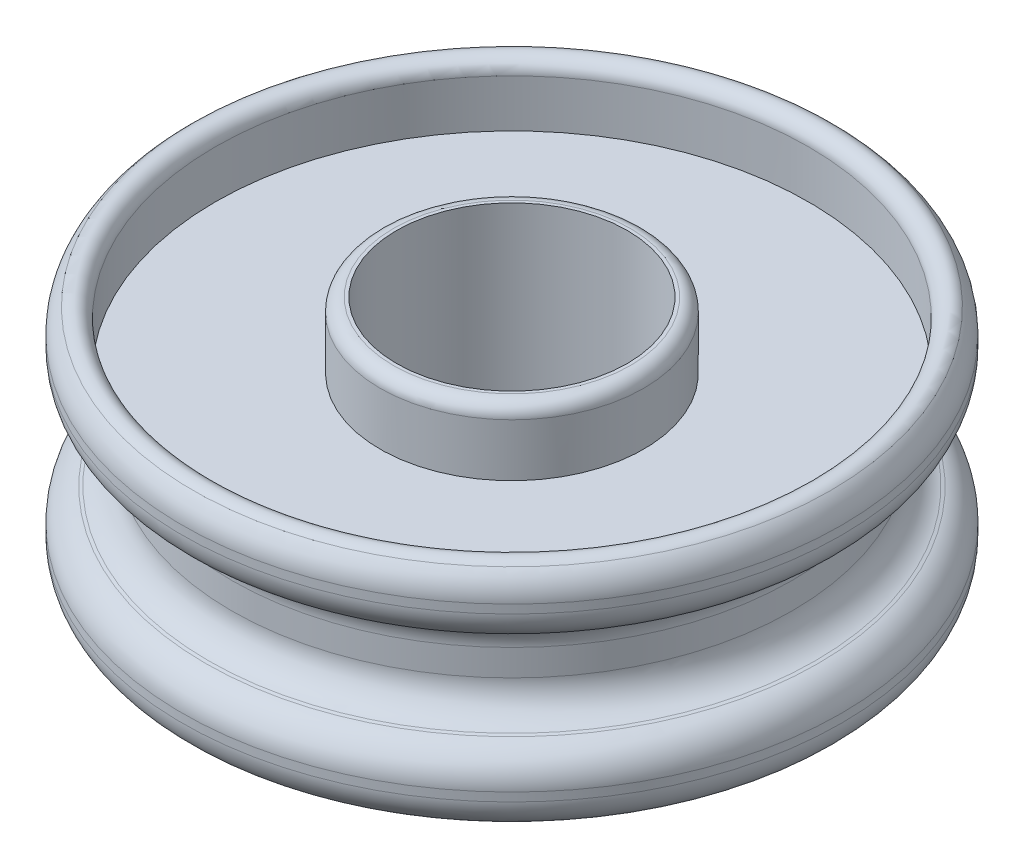
SolidWorks part; units mm, degrees
ref_plane "Front Plane" through (0, 0, 0) normal (0, 0, 1) x (1, 0, 0)
ref_plane "Top Plane" through (0, 0, 0) normal (0, 1, 0) x (1, 0, 0)
ref_plane "Right Plane" through (0, 0, 0) normal (1, 0, 0) x (0, 0, -1)
sketch "Sketch1" plane through (0, 0, 0) normal (0, 0, 1) x (1, 0, 0)
  line L0 (-1819.5005, 0) -> (89155.5226, 0) construction
  line L1 (0, -1819.5005) -> (0, 89155.5226) construction
  line L2 (17.5, 0) -> (45, 0)
  line L3 (50, -5) -> (50, -6.3066)
  line L4 (46.4698, -11.0857) -> (46.0302, -11.2209)
  line L5 (42.5, -16) -> (42.5, -20)
  line L6 (-957.5, -18) -> (49042.5, -18) construction
  line L7 (46.4698, -24.9143) -> (46.0302, -24.7791)
  line L8 (17.5, -36) -> (45, -36)
  line L9 (17.5, 0) -> (17.5, -36)
  line L10 (50, -29.6934) -> (50, -31)
  line L11 (50, -29.6934) -> (50, -31)
  arc A0 (42.5, -16) -> (46.0302, -11.2209) centre (47.5, -16) cw
  arc A1 (46.4698, -11.0857) -> (50, -6.3066) centre (45, -6.3066) ccw
  arc A2 (50, -5) -> (45, 0) centre (45, -5) ccw
  arc A3 (42.5, -20) -> (46.0302, -24.7791) centre (47.5, -20) ccw
  arc A4 (46.4698, -24.9143) -> (50, -29.6934) centre (45, -29.6934) cw
  arc A5 (50, -31) -> (45, -36) centre (45, -31) cw
  point P14 (50, -10)
  point P17 (50, 0)
  point P21 (42.5, -18)
  dimension "D5" = 5
  dimension "D1" = 50
  dimension "D2" = 17.5
  dimension "D3" = 10
  dimension "D4" = 42.5
  dimension "D6" = 2
  dimension "D7" = 6
revolve "Revolve1" add sketch "Sketch1" angle 360 about L1
sketch "Sketch2" plane through (0, 0, 0) normal (0, 1, 0) x (1, 0, 0)
  circle A0 centre (0, 0) radius 73.789
  circle A1 centre (0, 0) radius 20
  circle A2 centre (0, 0) radius 45 construction
  circle A3 centre (0, 0) radius 45
  dimension "D1" = 40
extrude "Cut-Extrude1" cut sketch "Sketch2" against normal blind 10 contours A3 | A1
fillet "Fillet2" radius 2 1 edges at (-45, 0, 0)
fillet "Fillet3" radius 2 1 edges at (-20, 0, 0)
sketch "Sketch3" plane through (0, -36, 0) normal (0, -1, 0) x (1, 0, 0)
  circle A0 centre (0, 0) radius 20
  circle A1 centre (0, 0) radius 45
  circle A2 centre (0, 0) radius 45
  dimension "D2" = 40
  dimension "D1" = 0
extrude "Cut-Extrude4" cut sketch "Sketch3" against normal blind 10
fillet "Fillet4" radius 2 1 edges at (20, -36, 0)
fillet "Fillet5" radius 2 1 edges at (45, -36, 0)
